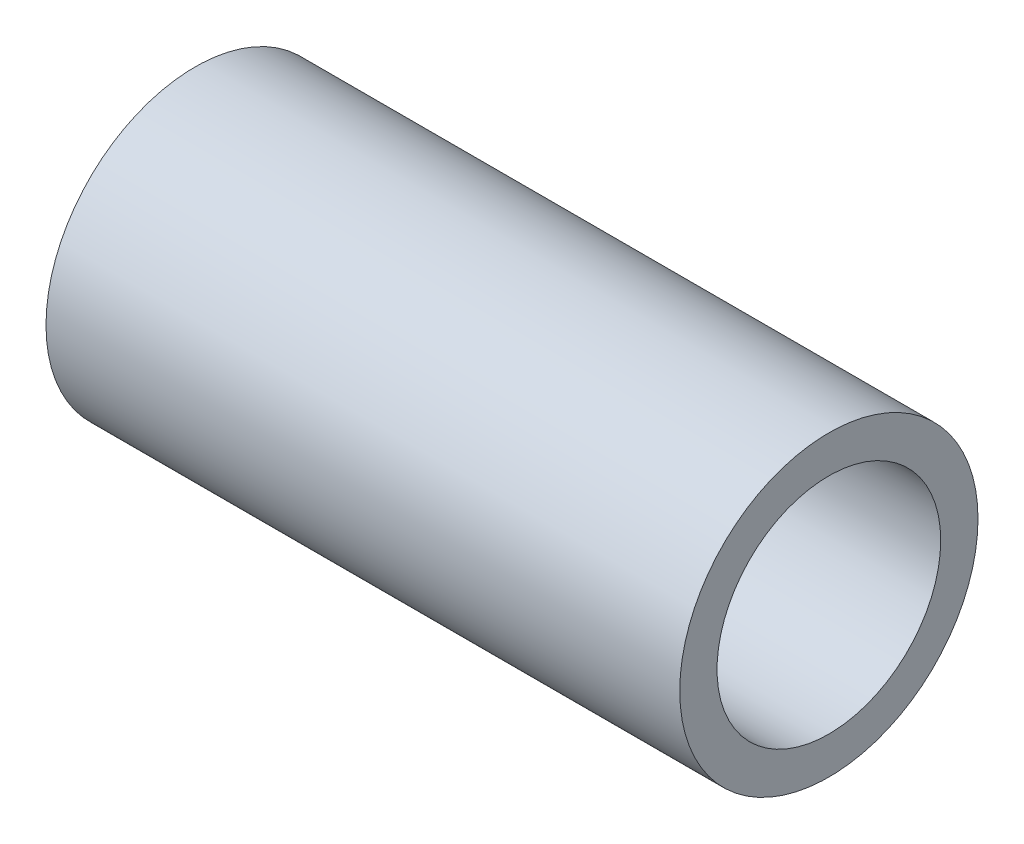
SolidWorks part; units mm, degrees
ref_plane "Front Plane" through (0, 0, 0) normal (0, 0, 1) x (1, 0, 0)
ref_plane "Top Plane" through (0, 0, 0) normal (0, 1, 0) x (1, 0, 0)
ref_plane "Right Plane" through (0, 0, 0) normal (1, 0, 0) x (0, 0, -1)
sketch "Sketch1" plane through (0, 0, 0) normal (1, 0, 0) x (0, 0, -1)
  circle A0 centre (0, 0) radius 4
  circle A1 centre (0, 0) radius 3
  dimension "D1" = 8
  dimension "D2" = 6
extrude "Boss-Extrude1" add sketch "Sketch1" along normal blind 17
